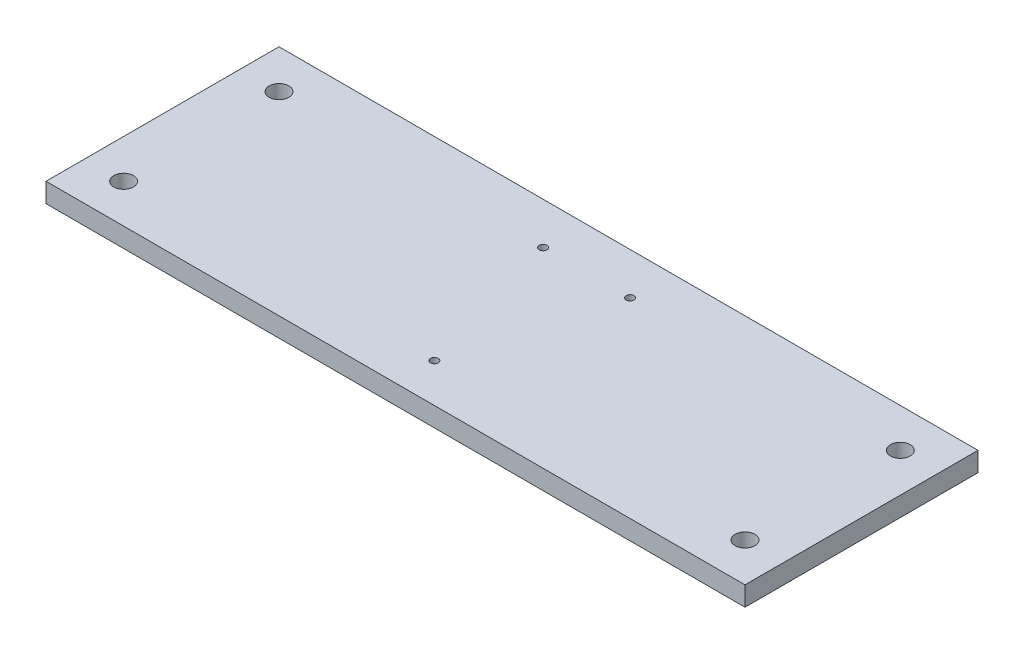
SolidWorks part; units mm, degrees
material "Brass"
ref_plane "Front Plane" through (0, 0, 0) normal (0, 0, 1) x (1, 0, 0)
ref_plane "Top Plane" through (0, 0, 0) normal (0, 1, 0) x (1, 0, 0)
ref_plane "Right Plane" through (0, 0, 0) normal (1, 0, 0) x (0, 0, -1)
sketch "Sketch1" plane through (0, 0, 0) normal (0, 1, 0) x (1, 0, 0)
  line L0 (0, 38.1) -> (0, -38.1) construction
  line L1 (114.3, -38.1) -> (-114.3, -38.1)
  line L2 (114.3, -38.1) -> (114.3, 38.1)
  line L3 (114.3, 38.1) -> (-114.3, 38.1)
  line L4 (-114.3, -38.1) -> (-114.3, 38.1)
  circle A0 centre (-14.2263, 24.3942) radius 1.27
  circle A1 centre (14.2263, 24.3942) radius 1.27
  circle A2 centre (0, -25.4) radius 1.27
  circle A3 centre (-101.6, 25.4) radius 3.2281
  circle A4 centre (101.6, 25.4) radius 3.2281
  circle A10 centre (101.6, -25.4) radius 3.2281
  circle A18 centre (-101.6, -25.4) radius 3.2281
  circle A61 centre (-101.6, -42.3333) radius 3.2281 [skipped]
  circle A62 centre (101.6, -42.3333) radius 3.2281 [skipped]
  circle A63 centre (-101.6, 8.4667) radius 3.2281 [skipped]
  circle A64 centre (-101.6, 0) radius 3.2281 [skipped]
  circle A65 centre (-101.6, -8.4667) radius 3.2281 [skipped]
  circle A66 centre (-101.6, -16.9333) radius 3.2281 [skipped]
  circle A67 centre (101.6, 8.4667) radius 3.2281 [skipped]
  circle A68 centre (101.6, 0) radius 3.2281 [skipped]
  circle A69 centre (101.6, -8.4667) radius 3.2281 [skipped]
  circle A70 centre (101.6, -16.9333) radius 3.2281 [skipped]
  circle A71 centre (-101.6, -33.8667) radius 3.2281 [skipped]
  circle A72 centre (-101.6, 16.9333) radius 3.2281 [skipped]
  circle A73 centre (101.6, 16.9333) radius 3.2281 [skipped]
  circle A74 centre (101.6, -33.8667) radius 3.2281 [skipped]
  point P0 (0, 0)
  point P14 (0, 0)
  dimension "D1" = 2.54
  dimension "D11" = 50.8
  dimension "D2" = 228.6
  dimension "D3" = 76.2
  dimension "D4" = 49.7942
  dimension "D5" = 28.4525
  dimension "D6" = 12.7
  dimension "D7" = 12.7
  dimension "D13" = 203.2
  dimension "D8" = 2
  dimension "D9" = 9
extrude "Boss-Extrude1" add sketch "Sketch1" along normal blind 6.35
